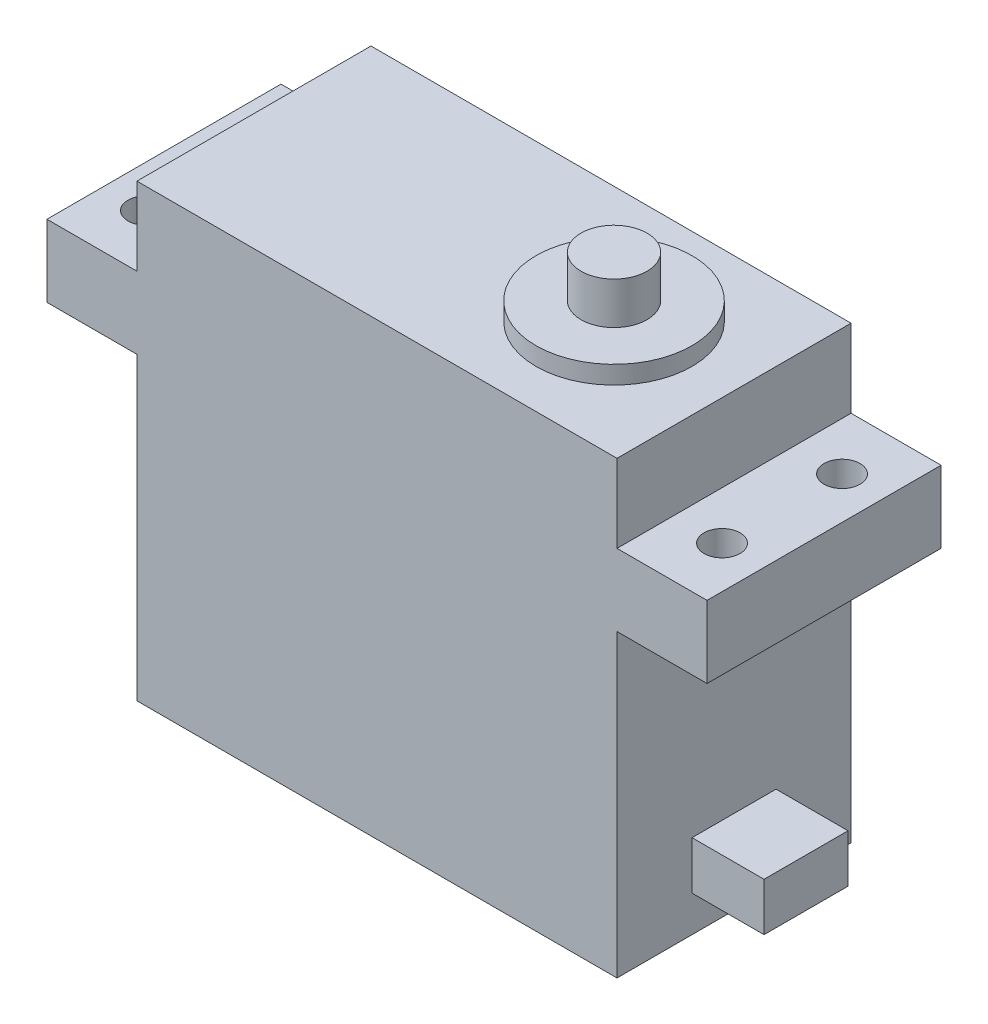
SolidWorks part; units mm, degrees
material "ABS"
ref_plane "Plan de face" through (0, 0, 0) normal (0, 0, 1) x (1, 0, 0)
ref_plane "Plan de dessus" through (0, 0, 0) normal (0, 1, 0) x (1, 0, 0)
ref_plane "Plan de droite" through (0, 0, 0) normal (1, 0, 0) x (0, 0, -1)
sketch "Esquisse1" plane through (0, 0, 0) normal (0, 1, 0) x (1, 0, 0)
  line L0 (0, 0) -> (10, 0) construction
  line L1 (-30, 9.75) -> (10, 9.75)
  line L2 (-30, 9.75) -> (-30, -9.75)
  line L3 (-30, -9.75) -> (10, -9.75)
  line L4 (10, 9.75) -> (10, -9.75)
  dimension "D1" = 40
  dimension "D2" = 19.5
  dimension "D3" = 10
extrude "Boss.-Extru.1" add sketch "Esquisse1" along normal blind 37.5
sketch "Esquisse2" plane through (0, 37.5, 0) normal (0, 1, 0) x (1, 0, 0)
  circle A0 centre (0, 0) radius 6.5
  dimension "D1" = 13
extrude "Boss.-Extru.2" add sketch "Esquisse2" along normal blind 1.5
sketch "Esquisse3" plane through (0, 39, 0) normal (0, 1, 0) x (1, 0, 0)
  circle A0 centre (0, 0) radius 2.75
  dimension "D1" = 5.5
extrude "Boss.-Extru.3" add sketch "Esquisse3" along normal blind 3.5
sketch "Esquisse4" plane through (0, 0, 0) normal (0, 1, 0) x (1, 0, 0)
  line L0 (-30, -9.75) -> (10, -9.75) construction
  line L1 (-37.5, -9.75) -> (17.5, -9.75)
  line L2 (-37.5, -9.75) -> (-37.5, 9.75)
  line L3 (-37.5, 9.75) -> (17.5, 9.75)
  line L4 (17.5, -9.75) -> (17.5, 9.75)
  line L5 (10, 9.75) -> (-30, 9.75) construction
  line L6 (-37.5, 0) -> (-10, 0) construction
  line L7 (-10, 0) -> (-10, 9.75) construction
  circle A0 centre (-34, 5) radius 1.5
  circle A1 centre (-34, -5) radius 1.5
  circle A2 centre (14, -5) radius 1.5
  circle A3 centre (14, 5) radius 1.5
  point P6 (-10, 9.75)
  dimension "D2" = 10
  dimension "D3" = 48
  dimension "D4" = 3
  dimension "D1" = 55
extrude "Boss.-Extru.4" add sketch "Esquisse4" along normal blind 6 from offset 25
sketch "Esquisse5" plane through (10, 0, 0) normal (1, 0, 0) x (0, 0, -1)
  line L0 (0, 3) -> (0, 0) construction
  line L1 (-3.5, 7) -> (3.5, 7)
  line L2 (-3.5, 7) -> (-3.5, 3)
  line L3 (-3.5, 3) -> (3.5, 3)
  line L4 (3.5, 7) -> (3.5, 3)
  line L5 (-9.75, 0) -> (9.75, 0) construction
  dimension "D1" = 3
  dimension "D2" = 4
  dimension "D3" = 7
extrude "Boss.-Extru.5" add sketch "Esquisse5" along normal blind 6
